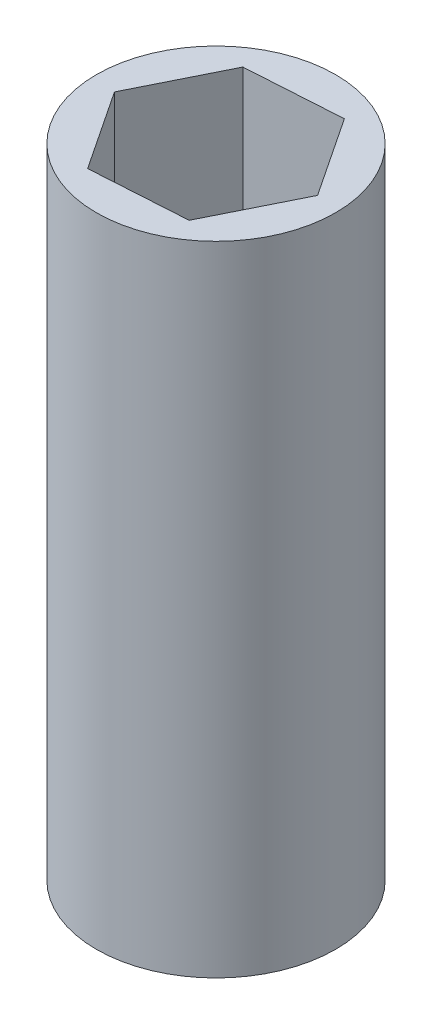
SolidWorks part; units mm, degrees
ref_plane "Front Plane" through (0, 0, 0) normal (0, 0, 1) x (1, 0, 0)
ref_plane "Top Plane" through (0, 0, 0) normal (0, 1, 0) x (1, 0, 0)
ref_plane "Right Plane" through (0, 0, 0) normal (1, 0, 0) x (0, 0, -1)
sketch "Sketch1" plane through (0, 0, 0) normal (0, 1, 0) x (1, 0, 0)
  line L1 (3.3933, 6.829) -> (-4.2175, 6.3532)
  line L2 (-4.2175, 6.3532) -> (-7.6108, -0.4758)
  line L3 (-7.6108, -0.4758) -> (-3.3933, -6.829)
  line L4 (-3.3933, -6.829) -> (4.2175, -6.3532)
  line L5 (4.2175, -6.3532) -> (7.6108, 0.4758)
  line L6 (7.6108, 0.4758) -> (3.3933, 6.829)
  circle A0 centre (0, 0) radius 6.604 construction
  circle A1 centre (0, 0) radius 9.525
  dimension "D2" = 19.05
  dimension "D1" = 13.208
extrude "Boss-Extrude1" add sketch "Sketch1" along normal blind 50.8
